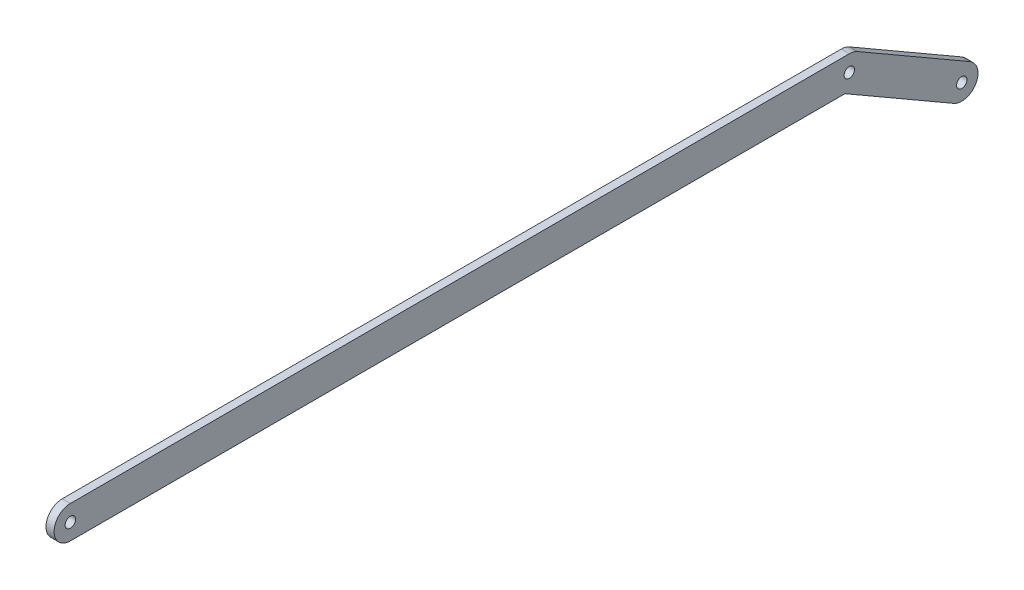
SolidWorks part; units mm, degrees
ref_plane "Front Plane" through (0, 0, 0) normal (0, 0, 1) x (1, 0, 0)
ref_plane "Top Plane" through (0, 0, 0) normal (0, 1, 0) x (1, 0, 0)
ref_plane "Right Plane" through (0, 0, 0) normal (1, 0, 0) x (0, 0, -1)
sketch "Sketch1" plane through (0, 0, 0) normal (1, 0, 0) x (0, 0, -1)
  line L0 (0, 0) -> (43.9941, -25.4) construction
  line L1 (3.175, 5.4993) -> (47.1691, -19.9007)
  line L2 (-3.175, -5.4993) -> (40.8191, -30.8993)
  line L3 (0, 0) -> (-304.8, 0) construction
  line L4 (0, -6.35) -> (-304.8, -6.35)
  line L5 (0, 6.35) -> (-304.8, 6.35)
  arc A0 (3.175, 5.4993) -> (-3.175, -5.4993) centre (0, 0) ccw
  arc A1 (40.8191, -30.8993) -> (47.1691, -19.9007) centre (43.9941, -25.4) ccw
  arc A2 (0, -6.35) -> (0, 6.35) centre (0, 0) ccw
  arc A3 (-304.8, 6.35) -> (-304.8, -6.35) centre (-304.8, 0) ccw
  circle A4 centre (-304.8, 0) radius 2.032
  circle A5 centre (43.9941, -25.4) radius 2.032
  circle A6 centre (0, 0) radius 2.032
  point P3 (21.997, -12.7)
  point P8 (-152.4, 0)
  dimension "D5" = 4.064
  dimension "D1" = 304.8
  dimension "D2" = 50.8
  dimension "D3" = 150
  dimension "D4" = 12.7
extrude "Boss-Extrude1" add sketch "Sketch1" along normal blind 3.175 contours A2 L4 L2 A1 L1 A5 | L4 A2 A0 L2 A6 | L5 A3 L4 L2 A0 A4
